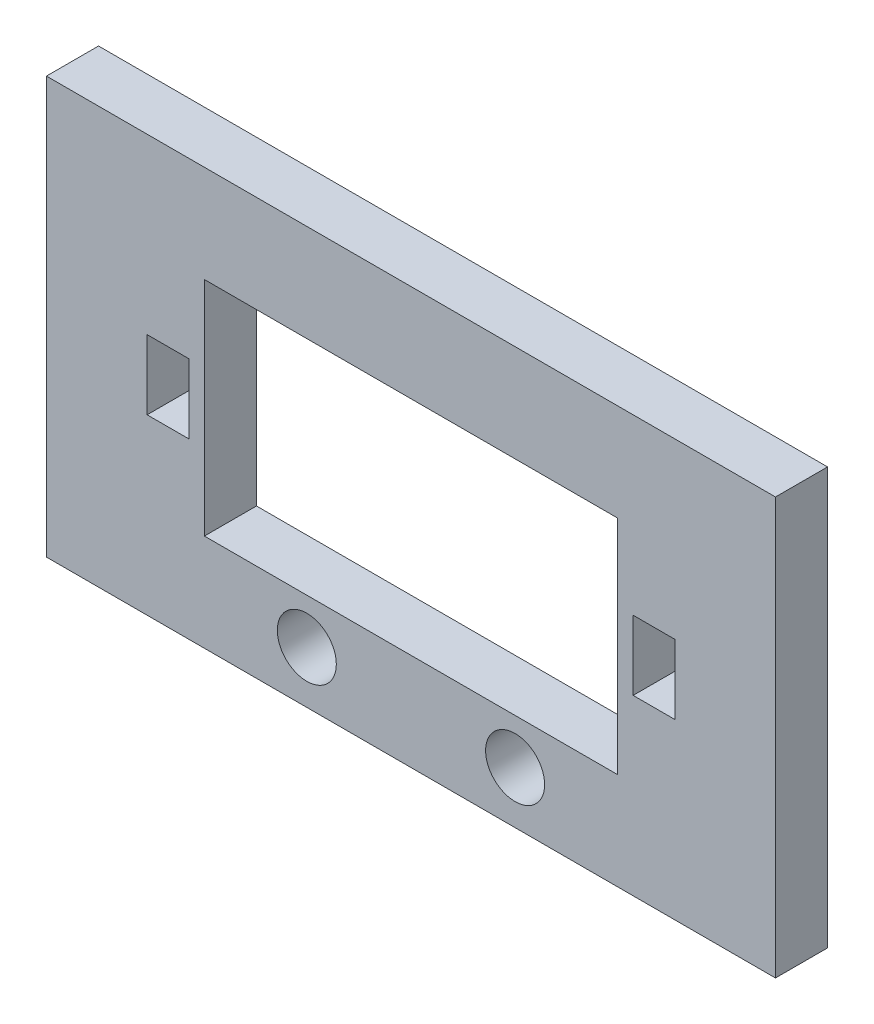
SolidWorks part; units mm, degrees
ref_plane "前视基准面" through (0, 0, 0) normal (0, 0, 1) x (1, 0, 0)
ref_plane "上视基准面" through (0, 0, 0) normal (0, 1, 0) x (1, 0, 0)
ref_plane "右视基准面" through (0, 0, 0) normal (1, 0, 0) x (0, 0, -1)
other "Configuration Table"
sketch "草图1" plane through (0, 0, 0) normal (0, 0, 1) x (1, 0, 0)
  line L1 (-21, -12) -> (21, -12)
  line L2 (-21, -12) -> (-21, 12)
  line L3 (-21, 12) -> (21, 12)
  line L4 (21, -12) -> (21, 12)
  line L6 (-11.9, -6.4) -> (11.9, -6.4)
  line L7 (-11.9, -6.4) -> (-11.9, 6.4)
  line L8 (-11.9, 6.4) -> (11.9, 6.4)
  line L9 (11.9, -6.4) -> (11.9, 6.4)
extrude "SG90_window23p8x12p8" add sketch "草图1" along normal blind 3
sketch "草图2" plane through (0, 0, 0) normal (0, 0, 1) x (1, 0, 0)
  line L1 (-15.2, -2) -> (-12.8, -2)
  line L2 (-15.2, -2) -> (-15.2, 2)
  line L3 (-15.2, 2) -> (-12.8, 2)
  line L4 (-12.8, -2) -> (-12.8, 2)
  line L6 (12.8, -2) -> (15.2, -2)
  line L7 (12.8, -2) -> (12.8, 2)
  line L8 (12.8, 2) -> (15.2, 2)
  line L9 (15.2, -2) -> (15.2, 2)
extrude "SG90_mount_slots_REFERENCE" cut sketch "草图2" against normal through all and the other way through all
sketch "草图3" plane through (0, 0, 0) normal (0, 0, 1) x (1, 0, 0)
  circle A0 centre (-6, -9) radius 1.7
  circle A1 centre (6, -9) radius 1.7
extrude "Adapter_M3_pair12_REFERENCE" cut sketch "草图3" against normal through all and the other way through all
